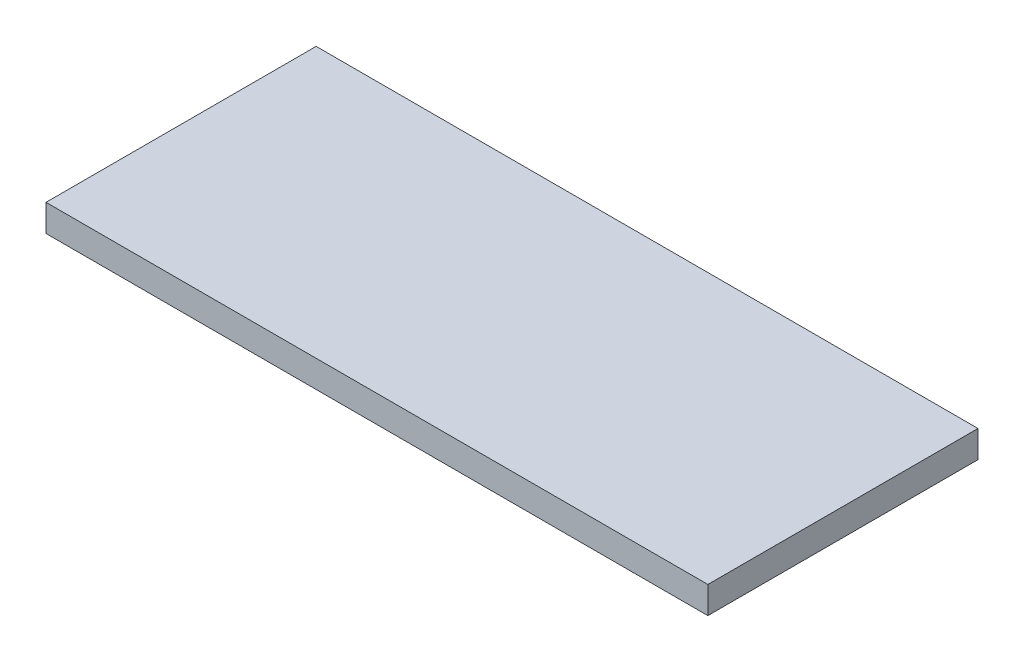
SolidWorks part; units mm, degrees
material "PCA9685"
ref_plane "Front Plane" through (0, 0, 0) normal (0, 0, 1) x (1, 0, 0)
ref_plane "Top Plane" through (0, 0, 0) normal (0, 1, 0) x (1, 0, 0)
ref_plane "Right Plane" through (0, 0, 0) normal (1, 0, 0) x (0, 0, -1)
sketch "Sketch1" plane through (0, 0, 0) normal (0, 1, 0) x (1, 0, 0)
  line L1 (-31.115, -12.7) -> (31.115, -12.7)
  line L2 (-31.115, -12.7) -> (-31.115, 12.7)
  line L3 (-31.115, 12.7) -> (31.115, 12.7)
  line L4 (31.115, -12.7) -> (31.115, 12.7)
  line L5 (-31.115, -12.7) -> (31.115, 12.7) construction
  line L6 (-31.115, 12.7) -> (31.115, -12.7) construction
  point P0 (0, 0)
extrude "Boss-Extrude1" add sketch "Sketch1" along normal blind 2.54
